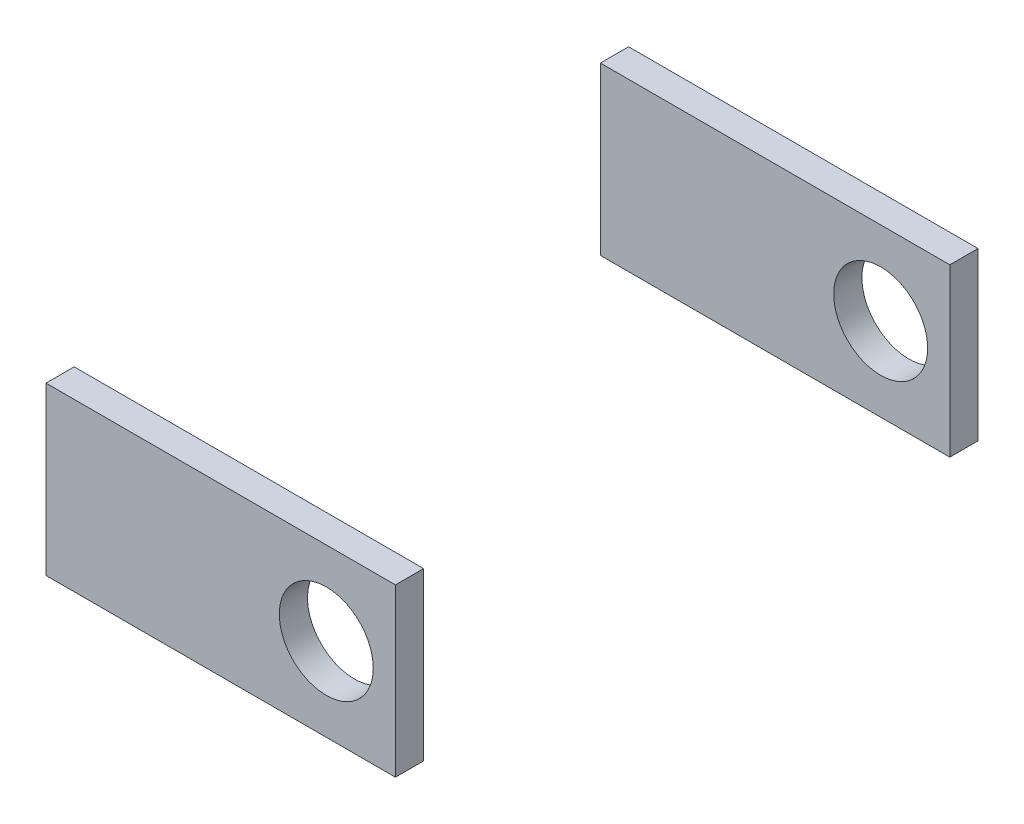
SolidWorks part; units mm, degrees
ref_plane "前视基准面" through (0, 0, 0) normal (0, 0, 1) x (1, 0, 0)
ref_plane "上视基准面" through (0, 0, 0) normal (0, 1, 0) x (1, 0, 0)
ref_plane "右视基准面" through (0, 0, 0) normal (1, 0, 0) x (0, 0, -1)
other "Configuration Table"
sketch "草图1" plane through (0, 0, 0) normal (0, 0, 1) x (1, 0, 0)
  circle A0 centre (0, 0) radius 2.5
  dimension "D1" = 5
extrude "凸台-拉伸1" add sketch "草图1" along normal blind 88.2
cosmetic thread "装饰螺纹线1" parameters "D1"=6.6, "D2"=4
ref_plane "基准面1" through (0, 0, 73.2) normal (0, 0, 1) x (1, 0, 0)
sketch "草图2" plane through (0, 0, 73.2) normal (0, 0, 1) x (1, 0, 0)
  circle A0 centre (0, 0) radius 12.5
  dimension "D1" = 25
extrude "凸台-拉伸2" add sketch "草图2" against normal blind 62
ref_plane "基准面2" through (0, 0, 73.2) normal (0, 0, 1) x (1, 0, 0)
sketch "草图3" plane through (0, 0, 73.2) normal (0, 0, 1) x (1, 0, 0)
  line L4 (0, 8.8652) -> (0, -8.8652)
  line L5 (0, -8.8652) -> (40, -8.8652)
  line L6 (40, -8.8652) -> (40, 8.8652)
  line L7 (40, 8.8652) -> (0, 8.8652)
  line L8 (-12.5, 0) -> (19.0607, 0) construction
  circle A1 centre (0, 0) radius 12.5 construction
  circle A2 centre (32.64, 0) radius 5
  dimension "D2" = 10
  dimension "D1" = 40
extrude "凸台-拉伸3" add sketch "草图3" against normal blind 3
cosmetic thread "装饰螺纹线2" parameters "D2"=11
pattern_linear "阵列(线性)1" count 2 spacing 59 along (0, 0, -1) of "凸台-拉伸3"
sketch "草图4" plane through (0, 0, 73.2) normal (0, 0, 1) x (1, 0, 0)
  line L0 (0, 0) -> (0, 12.3344)
  line L1 (32.64, 0) -> (32.64, 15.3929)
sketch "草图5" plane through (0, 0, 73.2) normal (0, 0, 1) x (1, 0, 0)
  line L0 (8.8124, 8.8652) -> (8.8124, -8.8652)
  line L1 (8.8124, -8.8652) -> (2.8124, -8.8652)
  line L2 (2.8124, -8.8652) -> (2.8124, 8.8652)
  line L3 (2.8124, 8.8652) -> (8.8124, 8.8652)
  arc A0 (8.8124, 8.8652) -> (8.8124, -8.8652) centre (0, 0) ccw
  arc M3 (8.8124, 8.8652) -> (8.8124, -8.8652) centre (0, 0) ccw
  circle M7 centre (0, 0) radius 2.5
  dimension "D1" = 6
extrude "切除-拉伸2" cut sketch "草图5" against normal through all contours L2 L3 L1 M3 M7 | M7
sketch "草图6" plane through (0, 0, 88.2) normal (0, 0, 1) x (1, 0, 0)
  circle A0 centre (0, 0) radius 2.5
extrude "切除-拉伸3" cut sketch "草图6" against normal through all
sketch "草图7" plane through (2.8124, 0, 0) normal (-1, 0, 0) x (0, 0, 1)
  line L0 (14.2, 8.8652) -> (14.2, -8.8652)
  line L1 (11.2, 8.8652) -> (73.2, 8.8652) construction
  line L2 (11.2, -8.8652) -> (73.2, -8.8652) construction
  line L3 (14.2, -8.8652) -> (70.2, -8.8652)
  line L4 (70.2, -8.8652) -> (70.2, 8.8652)
  line L5 (70.2, 8.8652) -> (14.2, 8.8652)
  line L6 (11.2, -8.8652) -> (11.2, 8.8652) construction
  line L7 (73.2, -9.7517) -> (73.2, 9.7517) construction
  dimension "D1" = 3
  dimension "D2" = 3
extrude "切除-拉伸4" cut sketch "草图7" against normal through all
